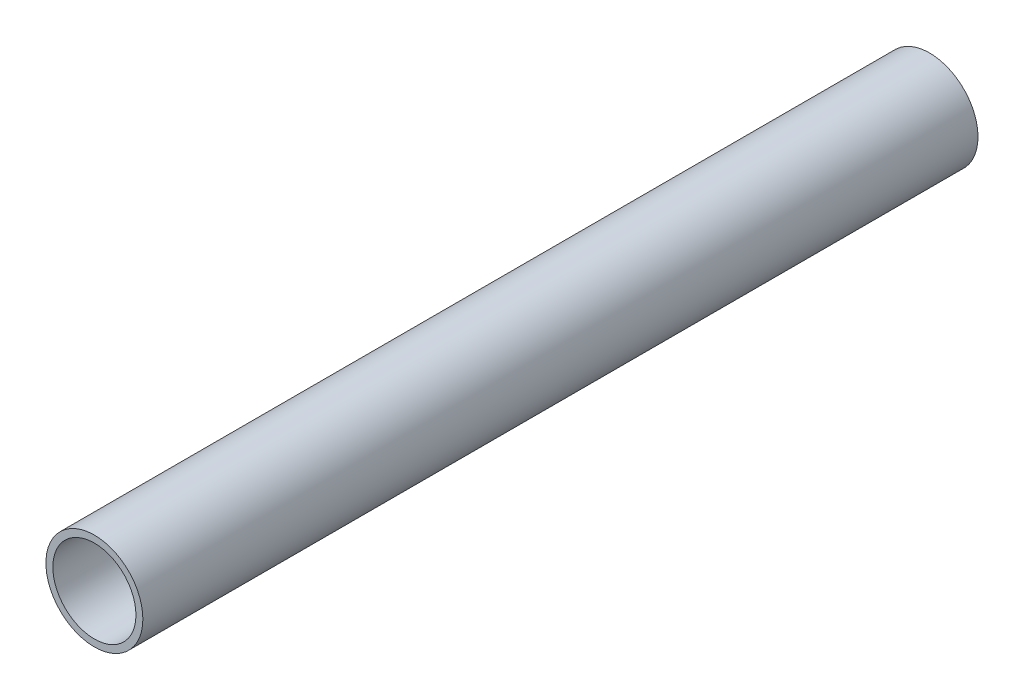
SolidWorks part; units mm, degrees
material "Thornel VCB-20 Carbon Cloth"
ref_plane "Front Plane" through (0, 0, 0) normal (0, 0, 1) x (1, 0, 0)
ref_plane "Top Plane" through (0, 0, 0) normal (0, 1, 0) x (1, 0, 0)
ref_plane "Right Plane" through (0, 0, 0) normal (1, 0, 0) x (0, 0, -1)
sketch "Sketch1" plane through (0, 0, 0) normal (0, 0, 1) x (1, 0, 0)
  circle A0 centre (0, 0) radius 9.525
  circle A1 centre (0, 0) radius 11.1125
  dimension "D1" = 19.05
  dimension "D2" = 22.225
extrude "Boss-Extrude1" add sketch "Sketch1" along normal mid plane 191.434
